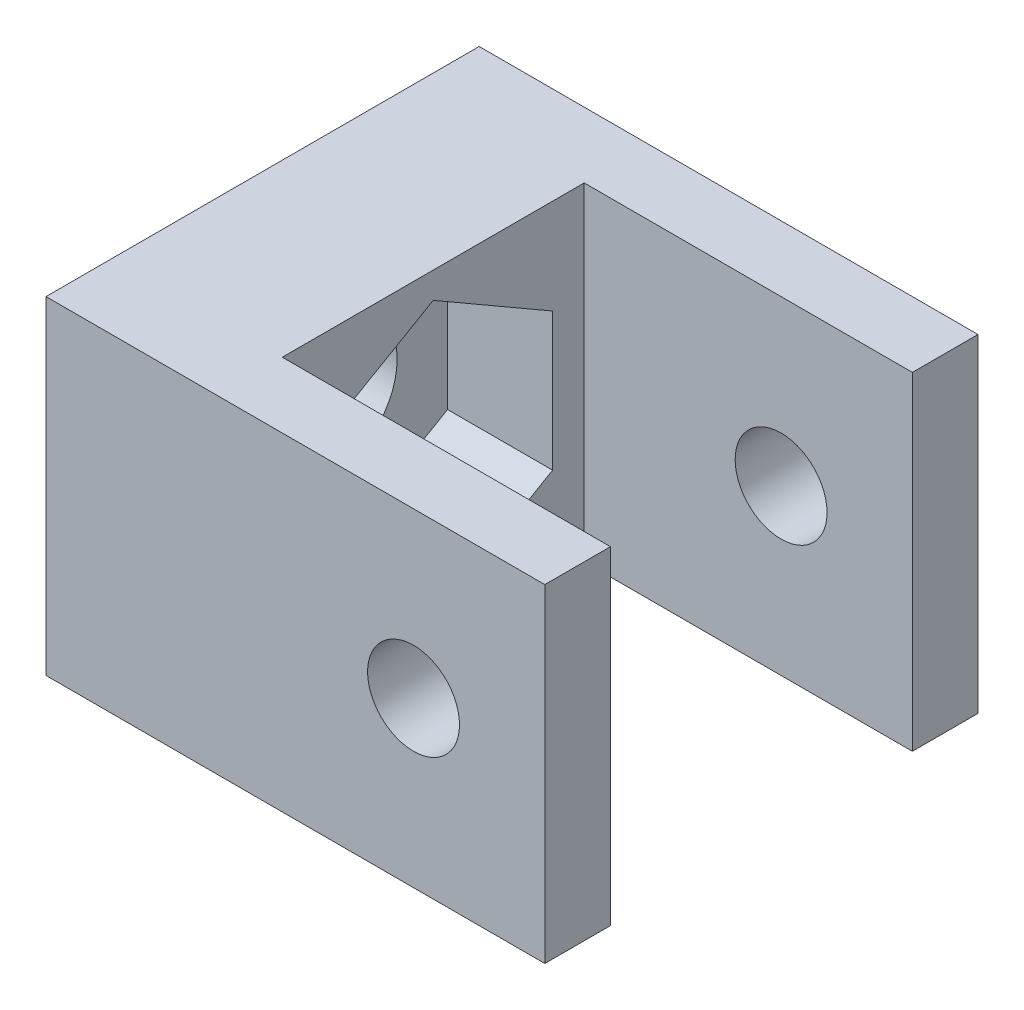
SolidWorks part; units mm, degrees
ref_plane "Plan de face" through (0, 0, 0) normal (0, 0, 1) x (1, 0, 0)
ref_plane "Plan de dessus" through (0, 0, 0) normal (0, 1, 0) x (1, 0, 0)
ref_plane "Plan de droite" through (0, 0, 0) normal (1, 0, 0) x (0, 0, -1)
sketch "Esquisse2" plane through (0, 0, 0) normal (0, 1, 0) x (1, 0, 0)
  line L0 (0, 0) -> (-38, 0)
  line L1 (-38, 0) -> (-38, -33)
  line L2 (-38, -33) -> (0, -33)
  line L3 (0, -33) -> (0, -28)
  line L4 (0, -28) -> (-25, -28)
  line L5 (-25, -28) -> (-25, -5)
  line L6 (-25, -5) -> (0, -5)
  line L7 (0, -5) -> (0, 0)
  dimension "D1" = 33
  dimension "D2" = 23
  dimension "D3" = 13
  dimension "D4" = 25
extrude "Boss.-Extru.1" add sketch "Esquisse2" along normal blind 25
sketch "Esquisse3" plane through (0, 0, 33) normal (0, 0, 1) x (1, 0, 0)
  line L0 (0, 25) -> (0, 0) construction
  line L1 (-38, 25) -> (0, 25) construction
  circle A0 centre (-10, 12.5) radius 3.5
  dimension "D1" = 7
  dimension "D2" = 10
  dimension "D3" = 12.5
extrude "Enlèv. mat.-Extru.1" cut sketch "Esquisse3" against normal through all
sketch "Esquisse4" plane through (-25, 0, 0) normal (1, 0, 0) x (0, 0, -1)
  line L0 (-5, 25) -> (-5, 0) construction
  line L1 (-28, 25) -> (-5, 25) construction
  circle A0 centre (-16.5, 12.5) radius 5.25
  dimension "D1" = 10.5
  dimension "D2" = 11.5
  dimension "D3" = 12.5
extrude "Enlèv. mat.-Extru.2" cut sketch "Esquisse4" against normal through all
sketch "Esquisse5" plane through (-25, 0, 0) normal (1, 0, 0) x (0, 0, -1)
  line L0 (-5, 25) -> (-5, 0) construction
  line L1 (-7.4067, 17.75) -> (-16.5, 23)
  line L2 (-16.5, 23) -> (-25.5933, 17.75)
  line L3 (-25.5933, 17.75) -> (-25.5933, 7.25)
  line L4 (-25.5933, 7.25) -> (-16.5, 2)
  line L5 (-16.5, 2) -> (-7.4067, 7.25)
  line L6 (-7.4067, 7.25) -> (-7.4067, 17.75)
  circle A0 centre (-16.5, 12.5) radius 9.0933 construction
  dimension "D1" = 10.5
extrude "Enlèv. mat.-Extru.3" cut sketch "Esquisse5" against normal blind 8
